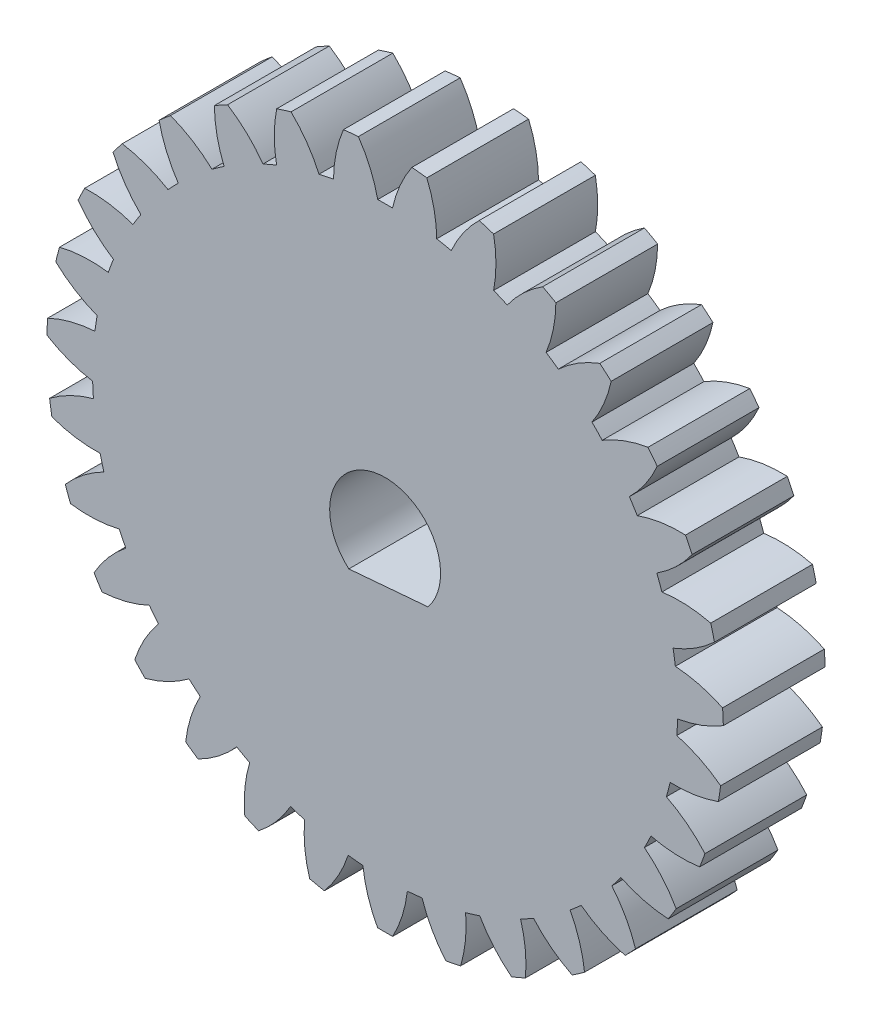
SolidWorks part; units mm, degrees
ref_plane "Front Plane" through (0, 0, 0) normal (0, 0, 1) x (1, 0, 0)
ref_plane "Top Plane" through (0, 0, 0) normal (0, 1, 0) x (1, 0, 0)
ref_plane "Right Plane" through (0, 0, 0) normal (1, 0, 0) x (0, 0, -1)
sketch "Model" plane through (0, 0, 0) normal (0, 0, 1) x (1, 0, 0)
  line L1 (-1.784, -2.0599) -> (2.1049, -1.7307)
  arc A124 (14.3694, -0.3649) -> (16.6183, 0.4718) centre (13.3283, 5.8738) ccw
  arc A125 (2.1049, -1.7307) -> (-1.784, -2.0599) centre (0, 0) ccw
  arc A126 (16.6183, 0.4718) -> (16.5808, 1.2118) centre (0, 0) ccw
  arc A127 (16.5808, 1.2118) -> (14.2587, 1.8167) centre (13.8542, -4.4953) ccw
  arc A128 (14.2587, 1.8167) -> (14.1487, 2.5351) centre (0, 0) ccw
  arc A129 (14.1487, 2.5351) -> (16.1831, 3.8074) centre (11.8731, 8.4366) ccw
  arc A130 (16.1831, 3.8074) -> (15.9974, 4.5247) centre (0, 0) ccw
  arc A131 (15.9974, 4.5247) -> (13.6011, 4.6498) centre (14.4755, -1.6145) ccw
  arc A132 (13.6011, 4.6498) -> (13.3487, 5.3313) centre (0, 0) ccw
  arc A133 (13.3487, 5.3313) -> (15.0854, 6.9871) centre (9.9318, 10.6539) ccw
  arc A134 (15.0854, 6.9871) -> (14.7591, 7.6523) centre (0, 0) ccw
  arc A135 (14.7591, 7.6523) -> (12.3867, 7.2925) centre (14.5042, 1.3325) ccw
  arc A136 (12.3867, 7.2925) -> (12.0023, 7.9093) centre (0, 0) ccw
  arc A137 (12.0023, 7.9093) -> (13.3701, 9.8808) centre (7.5838, 12.4351) ccw
  arc A138 (13.3701, 9.8808) -> (12.9166, 10.4667) centre (0, 0) ccw
  arc A139 (12.9166, 10.4667) -> (10.6652, 9.6367) centre (13.939, 4.2249) ccw
  arc A140 (10.6652, 9.6367) -> (10.1645, 10.1634) centre (0, 0) ccw
  arc A141 (10.1645, 10.1634) -> (11.1075, 12.3699) centre (4.9254, 13.7072) ccw
  arc A142 (11.1075, 12.3699) -> (10.5453, 12.8525) centre (0, 0) ccw
  arc A143 (10.5453, 12.8525) -> (8.507, 11.5863) centre (12.8032, 6.9443) ccw
  arc A144 (8.507, 11.5863) -> (7.9105, 12.0015) centre (0, 0) ccw
  arc A145 (7.9105, 12.0015) -> (8.3901, 14.3526) centre (2.0654, 14.4181) ccw
  arc A146 (8.3901, 14.3526) -> (7.7422, 14.7122) centre (0, 0) ccw
  arc A147 (7.7422, 14.7122) -> (6.0006, 13.0616) centre (11.1433, 9.3794) ccw
  arc A148 (6.0006, 13.0616) -> (5.3327, 13.3482) centre (0, 0) ccw
  arc A149 (5.3327, 13.3482) -> (5.3291, 15.7477) centre (-0.8792, 14.5387) ccw
  arc A150 (5.3291, 15.7477) -> (4.6222, 15.9695) centre (0, 0) ccw
  arc A151 (4.6222, 15.9695) -> (3.2485, 14.0021) centre (9.0271, 11.4305) ccw
  arc A152 (3.2485, 14.0021) -> (2.5366, 14.1484) centre (0, 0) ccw
  arc A153 (2.5366, 14.1484) -> (2.0501, 16.4981) centre (-3.7878, 14.0641) ccw
  arc A154 (2.0501, 16.4981) -> (1.3129, 16.5731) centre (0, 0) ccw
  arc A155 (1.3129, 16.5731) -> (0.3634, 14.3694) centre (6.5414, 13.0137) ccw
  arc A156 (0.3634, 14.3694) -> (-0.3634, 14.3694) centre (0, 0) ccw
  arc A157 (-0.3634, 14.3694) -> (-1.3129, 16.5731) centre (-6.5414, 13.0137) ccw
  arc A158 (-1.3129, 16.5731) -> (-2.0501, 16.4981) centre (0, 0) ccw
  arc A159 (-2.0501, 16.4981) -> (-2.5366, 14.1484) centre (3.7878, 14.0641) ccw
  arc A160 (-2.5366, 14.1484) -> (-3.2485, 14.0021) centre (0, 0) ccw
  arc A161 (-3.2485, 14.0021) -> (-4.6222, 15.9695) centre (-9.0271, 11.4305) ccw
  arc A162 (-4.6222, 15.9695) -> (-5.3291, 15.7477) centre (0, 0) ccw
  arc A163 (-5.3291, 15.7477) -> (-5.3327, 13.3482) centre (0.8792, 14.5387) ccw
  arc A164 (-5.3327, 13.3482) -> (-6.0006, 13.0616) centre (0, 0) ccw
  arc A165 (-6.0006, 13.0616) -> (-7.7422, 14.7122) centre (-11.1433, 9.3794) ccw
  arc A166 (-7.7422, 14.7122) -> (-8.3901, 14.3526) centre (0, 0) ccw
  arc A167 (-8.3901, 14.3526) -> (-7.9105, 12.0015) centre (-2.0654, 14.4181) ccw
  arc A168 (-7.9105, 12.0015) -> (-8.507, 11.5863) centre (0, 0) ccw
  arc A169 (-8.507, 11.5863) -> (-10.5453, 12.8525) centre (-12.8032, 6.9443) ccw
  arc A170 (-10.5453, 12.8525) -> (-11.1075, 12.3699) centre (0, 0) ccw
  arc A171 (-11.1075, 12.3699) -> (-10.1645, 10.1634) centre (-4.9254, 13.7072) ccw
  arc A172 (-10.1645, 10.1634) -> (-10.6652, 9.6367) centre (0, 0) ccw
  arc A173 (-10.6652, 9.6367) -> (-12.9166, 10.4667) centre (-13.939, 4.2249) ccw
  arc A174 (-12.9166, 10.4667) -> (-13.3701, 9.8808) centre (0, 0) ccw
  arc A175 (-13.3701, 9.8808) -> (-12.0023, 7.9093) centre (-7.5838, 12.4351) ccw
  arc A176 (-12.0023, 7.9093) -> (-12.3867, 7.2925) centre (0, 0) ccw
  arc A177 (-12.3867, 7.2925) -> (-14.7591, 7.6523) centre (-14.5042, 1.3325) ccw
  arc A178 (-14.7591, 7.6523) -> (-15.0854, 6.9871) centre (0, 0) ccw
  arc A179 (-15.0854, 6.9871) -> (-13.3487, 5.3313) centre (-9.9318, 10.6539) ccw
  arc A180 (-13.3487, 5.3313) -> (-13.6011, 4.6498) centre (0, 0) ccw
  arc A181 (-13.6011, 4.6498) -> (-15.9974, 4.5247) centre (-14.4755, -1.6145) ccw
  arc A182 (-15.9974, 4.5247) -> (-16.1831, 3.8074) centre (0, 0) ccw
  arc A183 (-16.1831, 3.8074) -> (-14.1487, 2.5351) centre (-11.8731, 8.4366) ccw
  arc A184 (-14.1487, 2.5351) -> (-14.2587, 1.8167) centre (0, 0) ccw
  arc A185 (-14.2587, 1.8167) -> (-16.5808, 1.2118) centre (-13.8542, -4.4953) ccw
  arc A186 (-16.5808, 1.2118) -> (-16.6183, 0.4718) centre (0, 0) ccw
  arc A187 (-16.6183, 0.4718) -> (-14.3694, -0.3649) centre (-13.3283, 5.8738) ccw
  arc A188 (-14.3694, -0.3649) -> (-14.3326, -1.0907) centre (0, 0) ccw
  arc A189 (-14.3326, -1.0907) -> (-16.4853, -2.1507) centre (-12.6657, -7.1921) ccw
  arc A190 (-16.4853, -2.1507) -> (-16.3731, -2.883) centre (0, 0) ccw
  arc A191 (-16.3731, -2.883) -> (-14.0018, -3.2499) centre (-14.2379, 3.0706) ccw
  arc A192 (-14.0018, -3.2499) -> (-13.8196, -3.9535) centre (0, 0) ccw
  arc A193 (-13.8196, -3.9535) -> (-15.7149, -5.4251) centre (-10.9587, -9.5945) ccw
  arc A194 (-15.7149, -5.4251) -> (-15.4576, -6.1199) centre (0, 0) ccw
  arc A195 (-15.4576, -6.1199) -> (-13.0609, -6.002) centre (-14.5645, 0.1417) ccw
  arc A196 (-13.0609, -6.002) -> (-12.7409, -6.6544) centre (0, 0) ccw
  arc A197 (-12.7409, -6.6544) -> (-14.3012, -8.4775) centre (-8.803, -11.604) ccw
  arc A198 (-14.3012, -8.4775) -> (-13.9092, -9.1062) centre (0, 0) ccw
  arc A199 (-13.9092, -9.1062) -> (-11.5854, -8.5082) centre (-14.2949, -2.793) ccw
  arc A200 (-11.5854, -8.5082) -> (-11.1406, -9.083) centre (0, 0) ccw
  arc A201 (-11.1406, -9.083) -> (-12.3019, -11.1827) centre (-6.2869, -13.1385) ccw
  arc A202 (-12.3019, -11.1827) -> (-11.7915, -11.7197) centre (0, 0) ccw
  arc A203 (-11.7915, -11.7197) -> (-9.6356, -10.6662) centre (-13.4401, -5.6134) ccw
  arc A204 (-9.6356, -10.6662) -> (-9.0841, -11.1396) centre (0, 0) ccw
  arc A205 (-9.0841, -11.1396) -> (-9.799, -13.4302) centre (-3.5134, -14.1351) ccw
  arc A206 (-9.799, -13.4302) -> (-9.1909, -13.8534) centre (0, 0) ccw
  arc A207 (-9.1909, -13.8534) -> (-7.2912, -12.3875) centre (-12.035, -8.2039) ccw
  arc A208 (-7.2912, -12.3875) -> (-6.6558, -12.7402) centre (0, 0) ccw
  arc A209 (-6.6558, -12.7402) -> (-6.895, -15.1278) centre (-0.5961, -14.553) ccw
  arc A210 (-6.895, -15.1278) -> (-6.2141, -15.42) centre (0, 0) ccw
  arc A211 (-6.2141, -15.42) -> (-4.6484, -13.6016) centre (-10.1372, -10.4586) ccw
  arc A212 (-4.6484, -13.6016) -> (-3.955, -13.8192) centre (0, 0) ccw
  arc A213 (-3.955, -13.8192) -> (-3.7086, -16.2061) centre (2.3456, -14.3751) ccw
  arc A214 (-3.7086, -16.2061) -> (-2.9829, -16.3552) centre (0, 0) ccw
  arc A215 (-2.9829, -16.3552) -> (-1.8152, -14.2589) centre (-7.8244, -12.2852) ccw
  arc A216 (-1.8152, -14.2589) -> (-1.0922, -14.3324) centre (0, 0) ccw
  arc A217 (-1.0922, -14.3324) -> (-0.3705, -16.6209) centre (5.1912, -13.6087) ccw
  arc A218 (-0.3705, -16.6209) -> (0.3705, -16.6209) centre (0, 0) ccw
  arc A219 (0.3705, -16.6209) -> (1.0922, -14.3324) centre (-5.1912, -13.6087) ccw
  arc A220 (1.0922, -14.3324) -> (1.8152, -14.2589) centre (0, 0) ccw
  arc A221 (1.8152, -14.2589) -> (2.9829, -16.3552) centre (7.8244, -12.2852) ccw
  arc A222 (2.9829, -16.3552) -> (3.7086, -16.2061) centre (0, 0) ccw
  arc A223 (3.7086, -16.2061) -> (3.955, -13.8192) centre (-2.3456, -14.3751) ccw
  arc A224 (3.955, -13.8192) -> (4.6484, -13.6016) centre (0, 0) ccw
  arc A225 (4.6484, -13.6016) -> (6.2141, -15.42) centre (10.1372, -10.4586) ccw
  arc A226 (6.2141, -15.42) -> (6.895, -15.1278) centre (0, 0) ccw
  arc A227 (6.895, -15.1278) -> (6.6558, -12.7402) centre (0.5961, -14.553) ccw
  arc A228 (6.6558, -12.7402) -> (7.2912, -12.3875) centre (0, 0) ccw
  arc A229 (7.2912, -12.3875) -> (9.1909, -13.8534) centre (12.035, -8.2039) ccw
  arc A230 (9.1909, -13.8534) -> (9.799, -13.4302) centre (0, 0) ccw
  arc A231 (9.799, -13.4302) -> (9.0841, -11.1396) centre (3.5134, -14.1351) ccw
  arc A232 (9.0841, -11.1396) -> (9.6356, -10.6662) centre (0, 0) ccw
  arc A233 (9.6356, -10.6662) -> (11.7915, -11.7197) centre (13.4401, -5.6134) ccw
  arc A234 (11.7915, -11.7197) -> (12.3019, -11.1827) centre (0, 0) ccw
  arc A235 (12.3019, -11.1827) -> (11.1406, -9.083) centre (6.2869, -13.1385) ccw
  arc A236 (11.1406, -9.083) -> (11.5854, -8.5082) centre (0, 0) ccw
  arc A237 (11.5854, -8.5082) -> (13.9092, -9.1062) centre (14.2949, -2.793) ccw
  arc A238 (13.9092, -9.1062) -> (14.3012, -8.4775) centre (0, 0) ccw
  arc A239 (14.3012, -8.4775) -> (12.7409, -6.6544) centre (8.803, -11.604) ccw
  arc A240 (12.7409, -6.6544) -> (13.0609, -6.002) centre (0, 0) ccw
  arc A241 (13.0609, -6.002) -> (15.4576, -6.1199) centre (14.5645, 0.1417) ccw
  arc A242 (15.4576, -6.1199) -> (15.7149, -5.4251) centre (0, 0) ccw
  arc A243 (15.7149, -5.4251) -> (13.8196, -3.9535) centre (10.9587, -9.5945) ccw
  arc A244 (13.8196, -3.9535) -> (14.0018, -3.2499) centre (0, 0) ccw
  arc A245 (14.0018, -3.2499) -> (16.3731, -2.883) centre (14.2379, 3.0706) ccw
  arc A246 (16.3731, -2.883) -> (16.4853, -2.1507) centre (0, 0) ccw
  arc A247 (16.4853, -2.1507) -> (14.3326, -1.0907) centre (12.6657, -7.1921) ccw
  arc A248 (14.3326, -1.0907) -> (14.3694, -0.3649) centre (0, 0) ccw
extrude "Boss-Extrude1" add sketch "Model" along normal blind 5
